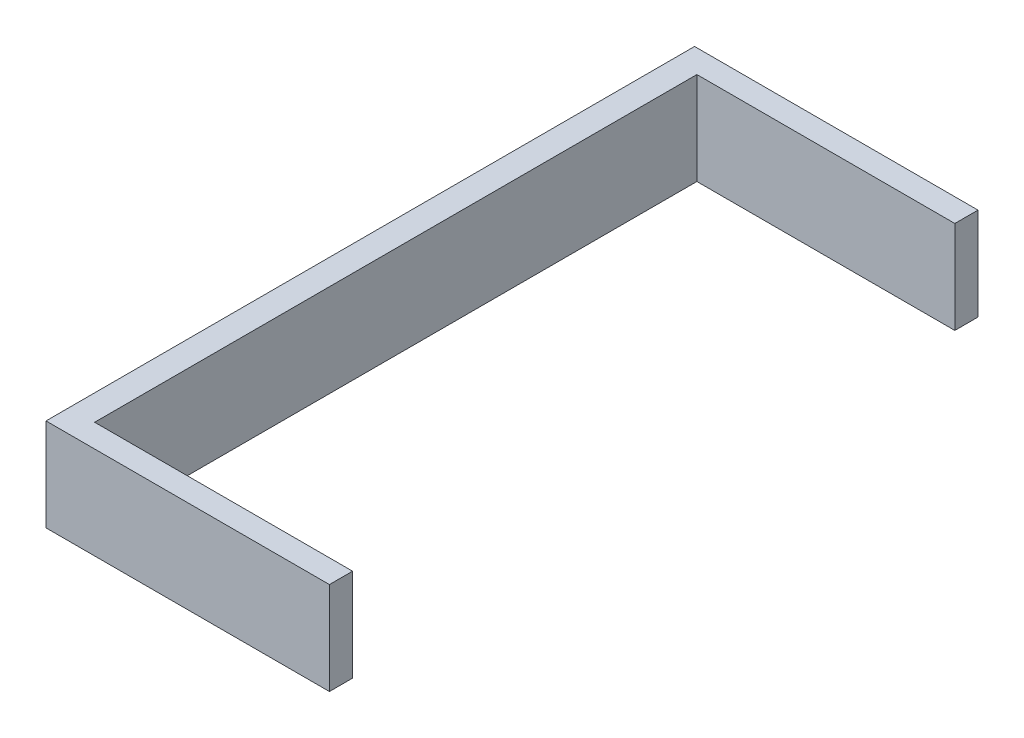
SolidWorks part; units mm, degrees
ref_plane "Front Plane" through (0, 0, 0) normal (0, 0, 1) x (1, 0, 0)
ref_plane "Top Plane" through (0, 0, 0) normal (0, 1, 0) x (1, 0, 0)
ref_plane "Right Plane" through (0, 0, 0) normal (1, 0, 0) x (0, 0, -1)
ref_plane "Plane1"
sketch "Sketch1" plane through (0, 0, 0) normal (0, 1, 0) x (-1, 0, 0)
  line L0 (-35.3568, 82.55) -> (35.3568, 82.55)
  line L1 (35.3568, 82.55) -> (35.3568, -82.55)
  line L2 (35.3568, -82.55) -> (-35.3568, -82.55)
  line L3 (-35.3568, -82.55) -> (-35.3568, -88.9)
  line L4 (-35.3568, -88.9) -> (42.3418, -88.9)
  line L5 (42.3418, -88.9) -> (42.3418, 88.9)
  line L6 (42.3418, 88.9) -> (-35.3568, 88.9)
  line L7 (-35.3568, 88.9) -> (-35.3568, 82.55)
  dimension "D1" = 165.1
  dimension "D2" = 177.8
  dimension "D3" = 77.6986
  dimension "D4" = 70.7136
  dimension "D5" = 70.7136
extrude "Extrusion1" add sketch "Sketch1" along normal blind 25.4
